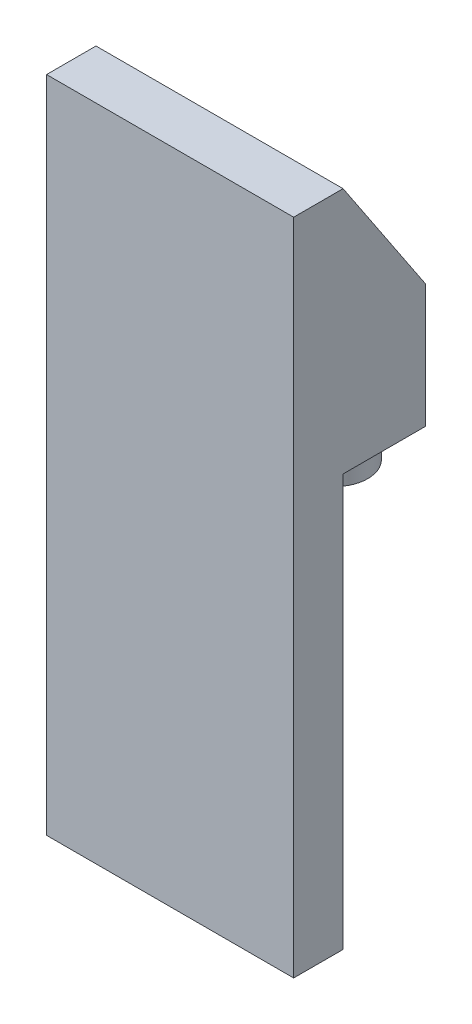
SolidWorks part; units mm, degrees
ref_plane "Front Plane" through (0, 0, 0) normal (0, 0, 1) x (1, 0, 0)
ref_plane "Top Plane" through (0, 0, 0) normal (0, 1, 0) x (1, 0, 0)
ref_plane "Right Plane" through (0, 0, 0) normal (1, 0, 0) x (0, 0, -1)
sketch "Sketch1" plane through (0, 0, 0) normal (0, 0, 1) x (1, 0, 0)
  line L1 (-7.0833, 11.9271) -> (7.9167, 11.9271)
  line L2 (-7.0833, 11.9271) -> (-7.0833, -28.0729)
  line L3 (-7.0833, -28.0729) -> (7.9167, -28.0729)
  line L4 (7.9167, 11.9271) -> (7.9167, -28.0729)
  dimension "D1" = 15
  dimension "D2" = 40
extrude "Boss-Extrude2" add sketch "Sketch1" along normal blind 3
sketch "Sketch2" plane through (0, 0, 0) normal (0, 0, -1) x (-1, 0, 0)
  line L0 (7.0833, 11.9271) -> (7.0833, -28.0729) construction
  line L1 (-7.9167, 11.9271) -> (7.0833, 11.9271)
  line L2 (-7.9167, 11.9271) -> (-7.9167, -3.0729)
  line L3 (-7.9167, -3.0729) -> (7.0833, -3.0729)
  line L4 (7.0833, 11.9271) -> (7.0833, -3.0729)
  dimension "D1" = 15
sketch "Sketch6" plane through (0, 0, 0) normal (0, 0, -1) x (-1, 0, 0)
extrude "Boss-Extrude5" add sketch "Sketch2" along normal blind 5
sketch "Sketch8" plane through (0, -3.0729, 0) normal (0, -1, 0) x (1, 0, 0)
sketch "Sketch12" plane through (-7.0833, 0, 0) normal (-1, 0, 0) x (0, 0, 1)
  line L3 (-5, -3.0729) -> (-5, 11.9271) construction
  line L6 (3, 11.9271) -> (-5, 11.9271) construction
  line L8 (-5, 11.9271) -> (-5, 4.4271)
  line L10 (0, 11.9271) -> (-5, 4.4271)
  line L11 (-5, 11.9271) -> (0, 11.9271)
extrude "Cut-Extrude9" cut sketch "Sketch12" against normal blind 15
sketch "Sketch14" plane through (0, 3.6699, -5.5048) normal (0, 0.5547, -0.8321) x (-1, 0, 0)
  line L0 (7.0833, 0.9101) -> (7.0833, 9.9239) construction
  line L1 (5.0833, 2.9101) -> (-5.9167, 2.9101)
  line L2 (5.0833, 2.9101) -> (5.0833, 3.4101)
  line L4 (-5.9167, 2.9101) -> (-5.9167, 3.4101)
  line L5 (-7.9167, 0.9101) -> (-7.9167, 9.9239) construction
  line L6 (-7.9167, 0.9101) -> (7.0833, 0.9101) construction
  line L8 (5.0833, 3.9101) -> (5.0833, 4.4101)
  line L9 (5.0833, 2.9101) -> (-5.9167, 2.9101)
  line L10 (5.0833, 2.9101) -> (5.0833, 3.4101)
  line L11 (5.0833, 3.4101) -> (-5.9167, 3.4101)
  line L12 (-5.9167, 2.9101) -> (-5.9167, 3.4101)
  line L13 (5.0833, 3.4101) -> (-5.9167, 3.4101)
  line L15 (5.0833, 3.9101) -> (-5.9167, 3.9101)
  line L17 (5.0833, 3.9101) -> (-5.9167, 3.9101)
  line L18 (5.0833, 3.9101) -> (5.0833, 4.4101)
  line L19 (5.0833, 4.4101) -> (-5.9167, 4.4101)
  line L20 (-5.9167, 3.9101) -> (-5.9167, 4.4101)
  line L21 (5.0833, 4.4101) -> (-5.9167, 4.4101)
  line L23 (5.0833, 4.9101) -> (-5.9167, 4.9101)
  line L25 (5.0833, 4.9101) -> (-5.9167, 4.9101)
  line L26 (5.0833, 4.9101) -> (5.0833, 5.4101)
  line L27 (5.0833, 5.4101) -> (-5.9167, 5.4101)
  line L28 (-5.9167, 4.9101) -> (-5.9167, 5.4101)
  line L29 (5.0833, 5.4101) -> (-5.9167, 5.4101)
  line L31 (5.0833, 5.9101) -> (-5.9167, 5.9101)
  line L33 (5.0833, 5.9101) -> (-5.9167, 5.9101)
  line L34 (5.0833, 5.9101) -> (5.0833, 6.4101)
  line L35 (5.0833, 6.4101) -> (-5.9167, 6.4101)
  line L36 (-5.9167, 5.9101) -> (-5.9167, 6.4101)
  line L37 (5.0833, 6.4101) -> (-5.9167, 6.4101)
  line L39 (5.0833, 6.9101) -> (-5.9167, 6.9101)
  line L41 (5.0833, 6.9101) -> (-5.9167, 6.9101)
  line L42 (5.0833, 6.9101) -> (5.0833, 7.4101)
  line L43 (5.0833, 7.4101) -> (-5.9167, 7.4101)
  line L44 (-5.9167, 6.9101) -> (-5.9167, 7.4101)
  line L45 (5.0833, 7.4101) -> (-5.9167, 7.4101)
  line L49 (-5.9167, 3.9101) -> (-5.9167, 4.4101)
  line L50 (-5.9167, 4.9101) -> (-5.9167, 5.4101)
  line L51 (5.0833, 4.9101) -> (5.0833, 5.4101)
  line L52 (5.0833, 5.9101) -> (5.0833, 6.4101)
  line L53 (-5.9167, 5.9101) -> (-5.9167, 6.4101)
  line L54 (-5.9167, 6.9101) -> (-5.9167, 7.4101)
  line L55 (5.0833, 6.9101) -> (5.0833, 7.4101)
  line L56 (5.0833, 7.9101) -> (5.0833, 7.9239)
  line L57 (-5.9167, 7.9101) -> (-5.9167, 7.9239)
  dimension "D1" = 2
  dimension "D2" = 2
  dimension "D3" = 2
  dimension "D6" = 0.5
  dimension "D7" = 0.5
  dimension "D8" = 0.5
  dimension "D9" = 0.5
  dimension "D10" = 0.5
  dimension "D11" = 0.5
  dimension "D12" = 0.5
  dimension "D13" = 0.5
  dimension "D14" = 0.5
extrude "Cut-Extrude10" cut sketch "Sketch14" against normal blind 5 contours L2 L11 L4 L1 | L20 L15 L8 L19 | L28 L23 L26 L27 | L36 L31 L34 L35 | L44 L39 L42 L43
sketch "Sketch17" plane through (0, -3.0729, 0) normal (0, -1, 0) x (-1, 0, 0)
  line L0 (7.0833, 5) -> (7.0833, 0) construction
  line L4 (6.0833, 5) -> (-1.9167, 5)
  line L6 (-7.9167, 5) -> (7.0833, 5) construction
  line L7 (4.0833, 0.5) -> (-4.9167, 0.5)
  line L8 (-4.9167, 4.5) -> (4.0833, 4.5)
  line L9 (-7.9167, 5) -> (-7.9167, 0) construction
  arc A5 (4.0833, 0.5) -> (4.0833, 4.5) centre (4.0833, 2.5) ccw
  arc A6 (-4.9167, 4.5) -> (-4.9167, 0.5) centre (-4.9167, 2.5) ccw
  point P14 (2.0833, 2.5)
  dimension "D3" = 3
  dimension "D1" = 4
  dimension "D2" = 4
  dimension "D4" = 3
extrude "Boss-Extrude9" add sketch "Sketch17" along normal blind 2 contours L8 A6 L7 A5
sketch "Sketch18" plane through (0, -5.0729, 0) normal (0, -1, 0) x (1, 0, 0)
  circle A0 centre (-4.0833, -2.5) radius 1.5
  circle A1 centre (4.9167, -2.5) radius 1.5
  arc A2 (-4.0833, -0.5) -> (-4.0833, -4.5) centre (-4.0833, -2.5) ccw construction
  arc A3 (4.9167, -4.5) -> (4.9167, -0.5) centre (4.9167, -2.5) ccw construction
  circle A4 centre (0.4167, -2.5) radius 1.5
  dimension "D1" = 3
  dimension "D2" = 0
  dimension "D3" = 0
extrude "Cut-Extrude11" cut sketch "Sketch18" against normal blind 10
